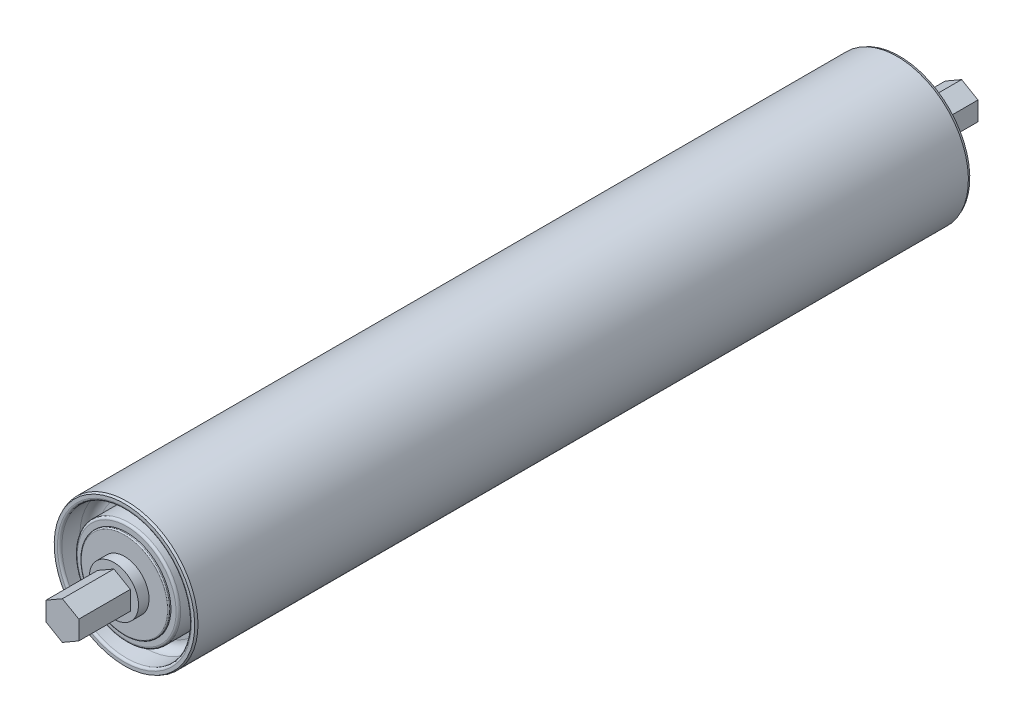
SolidWorks part; units mm, degrees
ref_plane "Front Plane" through (0, 0, 0) normal (0, 0, 1) x (1, 0, 0)
ref_plane "Top Plane" through (0, 0, 0) normal (0, 1, 0) x (1, 0, 0)
ref_plane "Right Plane" through (0, 0, 0) normal (1, 0, 0) x (0, 0, -1)
sketch "Sketch1" plane through (0, 0, 0) normal (1, 0, 0) x (0, 0, -1)
  line L0 (-152.4, 0) -> (152.4, 0) construction
  line L1 (-130.5719, 24.13) -> (130.5719, 24.13)
  line L2 (0, 24.13) -> (0, 0) construction
  line L3 (-152.4, 0) -> (-152.4, 5.5562)
  line L4 (-152.4, 5.5562) -> (-130.5719, 5.5562)
  line L5 (-136.525, 5.5562) -> (-136.525, -5.5562) construction
  line L6 (136.525, 5.5562) -> (136.525, -5.5562) construction
  line L7 (-136.525, -5.5562) -> (136.525, -5.5562) construction
  line L8 (-130.5719, 24.13) -> (-130.5719, 0) construction
  line L9 (-134.9375, 8.3344) -> (-134.9375, 0)
  line L10 (-134.9375, 8.3344) -> (-130.5719, 8.3344)
  line L11 (134.9375, 8.3344) -> (130.5719, 8.3344)
  line L12 (134.9375, 8.3344) -> (134.9375, 0)
  line L13 (152.4, 5.5563) -> (130.5719, 5.5563)
  line L14 (152.4, 0) -> (152.4, 5.5563)
  line L15 (-131.3656, 15.0019) -> (-130.6036, 15.0019) construction
  line L16 (-130.5719, 24.13) -> (-131.3656, 23.8125)
  line L17 (-131.3656, 23.8125) -> (-131.3656, 8.3344)
  line L18 (130.5719, 24.13) -> (131.3656, 23.8125)
  line L19 (131.3656, 23.8125) -> (131.3656, 8.3344)
  line L20 (-130.6036, 15.0019) -> (-130.6036, 17.5022) construction
  line L22 (-130.6036, 17.5022) -> (-121.4438, 17.5022) construction
  line L23 (-121.4438, 17.5022) -> (-121.4438, 21.971) construction
  line L24 (-121.4438, 21.971) -> (-131.3656, 21.971) construction
  arc A1 (-124.4918, 21.971) -> (-121.4438, 18.923) centre (-124.4918, 18.923) cw construction
  arc A2 (-131.3656, 22.733) -> (-130.6036, 21.971) centre (-130.6036, 22.733) ccw construction
  arc A3 (-130.6036, 16.7402) -> (-129.8416, 17.5022) centre (-129.8416, 16.7402) cw construction
  arc A4 (-131.3656, 14.6209) -> (-130.9846, 15.0019) centre (-130.9846, 14.6209) cw construction
  point P11 (-136.525, 0)
  point P12 (136.525, 0)
  point P13 (0, -5.5562)
  point P24 (-106.68, 0)
  point P27 (106.68, 0)
  point P32 (-121.4438, 19.7366)
  dimension "D14" = 3.048
  dimension "D15" = 0.762
  dimension "D16" = 0.381
  dimension "Overall Width" = 304.8
  dimension "Rollar Diameter" = 48.26
  dimension "Hex Axle Size" = 11.1125
  dimension "BF" = 273.05
  dimension "D2" = 16.6687
  dimension "D1" = 1.5875
  dimension "D5" = 15.875
  dimension "D6" = 45.72
  dimension "D7" = 45.72
  dimension "D3" = 4.3656
  dimension "D8" = 47.625
  dimension "D10" = 0.762
  dimension "D9" = 35.0044
  dimension "D11" = 30.0038
  dimension "D12" = 43.942
  dimension "D13" = 13.4937
  dimension "Rollar Width" = 262.7312
sketch "Sketch5" plane through (0, 0, 0) normal (0, 0, 1) x (1, 0, 0)
  circle A0 centre (0, 0) radius 24.13
  dimension "D1" = 48.26
sketch "Sketch3" plane through (0, 0, 0) normal (1, 0, 0) x (0, 0, -1)
  line L0 (152.4, 5.5563) -> (130.5719, 5.5563) construction
  line L1 (152.4, 0) -> (152.4, 5.5563) construction
  line L2 (-152.4, 0) -> (-152.4, 5.5562) construction
  line L3 (-152.4, 5.5562) -> (-130.5719, 5.5562) construction
  line L4 (131.3656, 23.8125) -> (131.3656, 8.3344) construction
  line L5 (130.5719, 24.13) -> (131.3656, 23.8125) construction
  line L6 (-130.5719, 24.13) -> (130.5719, 24.13) construction
  line L7 (-130.5719, 24.13) -> (-131.3656, 23.8125) construction
  line L8 (-131.3656, 23.8125) -> (-131.3656, 8.3344) construction
  line L9 (134.9375, 8.3344) -> (130.5719, 8.3344) construction
  line L10 (134.9375, 8.3344) -> (134.9375, 0) construction
  line L11 (-134.9375, 8.3344) -> (-134.9375, 0) construction
  line L12 (-134.9375, 8.3344) -> (-130.5719, 8.3344) construction
  line L13 (152.4, 5.5563) -> (134.9375, 5.5563)
  line L14 (152.4, 0) -> (152.4, 5.5563)
  line L15 (-152.4, 0) -> (-152.4, 5.5562)
  line L16 (-152.4, 5.5562) -> (-134.9375, 5.5562)
  line L17 (131.3656, 23.8125) -> (131.3656, 8.3344)
  line L18 (130.5719, 24.13) -> (131.3656, 23.8125)
  line L19 (-130.5719, 24.13) -> (130.5719, 24.13)
  line L20 (-130.5719, 24.13) -> (-131.3656, 23.8125)
  line L21 (-131.3656, 23.8125) -> (-131.3656, 8.3344)
  line L22 (134.9375, 8.3344) -> (131.3656, 8.3344)
  line L23 (134.9375, 8.3344) -> (134.9375, 5.5563)
  line L24 (-134.9375, 8.3344) -> (-134.9375, 5.5562)
  line L25 (-134.9375, 8.3344) -> (-131.3656, 8.3344)
  line L26 (-152.4, 0) -> (152.4, 0)
revolve "Revolve1" add sketch "Sketch3" angle 360 about L0
sketch "Sketch4" plane through (0, 0, 152.4) normal (0, 0, 1) x (1, 0, 0)
  line L1 (0, 6.4158) -> (-5.5562, 3.2079)
  line L2 (-5.5562, 3.2079) -> (-5.5562, -3.2079)
  line L3 (-5.5562, -3.2079) -> (0, -6.4158)
  line L4 (0, -6.4158) -> (5.5562, -3.2079)
  line L5 (5.5562, -3.2079) -> (5.5562, 3.2079)
  line L6 (5.5562, 3.2079) -> (0, 6.4158)
  circle A0 centre (0, 0) radius 5.5562 construction
extrude "Boss-Extrude1" add sketch "Sketch4" against normal up to surface (304.8 mm away) up to face at (0, -5.5562, -152.4)
sketch "Sketch6" plane through (0, 0, 0) normal (1, 0, 0) x (0, 0, -1)
  line L0 (-121.4438, 21.971) -> (-131.3656, 21.971) construction
  line L1 (-121.4438, 17.5022) -> (-121.4438, 21.971) construction
  line L2 (-130.6036, 17.5022) -> (-121.4438, 17.5022) construction
  line L3 (-130.6036, 15.0019) -> (-130.6036, 17.5022) construction
  line L4 (-131.3656, 15.0019) -> (-130.6036, 15.0019) construction
  line L5 (-124.4918, 21.971) -> (-130.6036, 21.971)
  line L6 (-121.4438, 17.5022) -> (-121.4438, 18.923)
  line L7 (-129.8416, 17.5022) -> (-121.4438, 17.5022)
  line L8 (-130.6036, 15.0019) -> (-130.6036, 16.7402)
  line L9 (-130.9846, 15.0019) -> (-130.6036, 15.0019)
  line L10 (-131.3656, 22.733) -> (-131.3656, 14.6209)
  arc A0 (-131.3656, 22.733) -> (-130.6036, 21.971) centre (-130.6036, 22.733) ccw construction
  arc A1 (-121.4438, 18.923) -> (-124.4918, 21.971) centre (-124.4918, 18.923) ccw construction
  arc A2 (-129.8416, 17.5022) -> (-130.6036, 16.7402) centre (-129.8416, 16.7402) ccw construction
  arc A3 (-130.9846, 15.0019) -> (-131.3656, 14.6209) centre (-130.9846, 14.6209) ccw construction
  arc A4 (-131.3656, 22.733) -> (-130.6036, 21.971) centre (-130.6036, 22.733) ccw
  arc A5 (-121.4438, 18.923) -> (-124.4918, 21.971) centre (-124.4918, 18.923) ccw
  arc A6 (-129.8416, 17.5022) -> (-130.6036, 16.7402) centre (-129.8416, 16.7402) ccw
  arc A7 (-130.9846, 15.0019) -> (-131.3656, 14.6209) centre (-130.9846, 14.6209) ccw
revolve "Cut-Revolve1" cut sketch "Sketch6" angle 360 about L0
mirror "Mirror2" about plane through (0, 0, 0) normal (0, 0, 1) of "Cut-Revolve1"
ref_plane "Contact Plane 1" through (0, 24.13, 0) normal (0, 1, 0) x (1, 0, 0)
equation "\"D2@Sketch1\"=\"Hex Axle Size@Sketch1\"*1.5"
equation "\"D7@Sketch1\"=\"D6@Sketch1\""
equation "\"D9@Sketch1\"=\"D2@Sketch1\"*2.1"
equation "\"D11@Sketch1\"=\"D2@Sketch1\"*1.8"
equation "\"D12@Sketch1\"=1.7+\"D10@Sketch1\""
equation "\"D16@Sketch1\"=\"D15@Sketch1\"/2"
